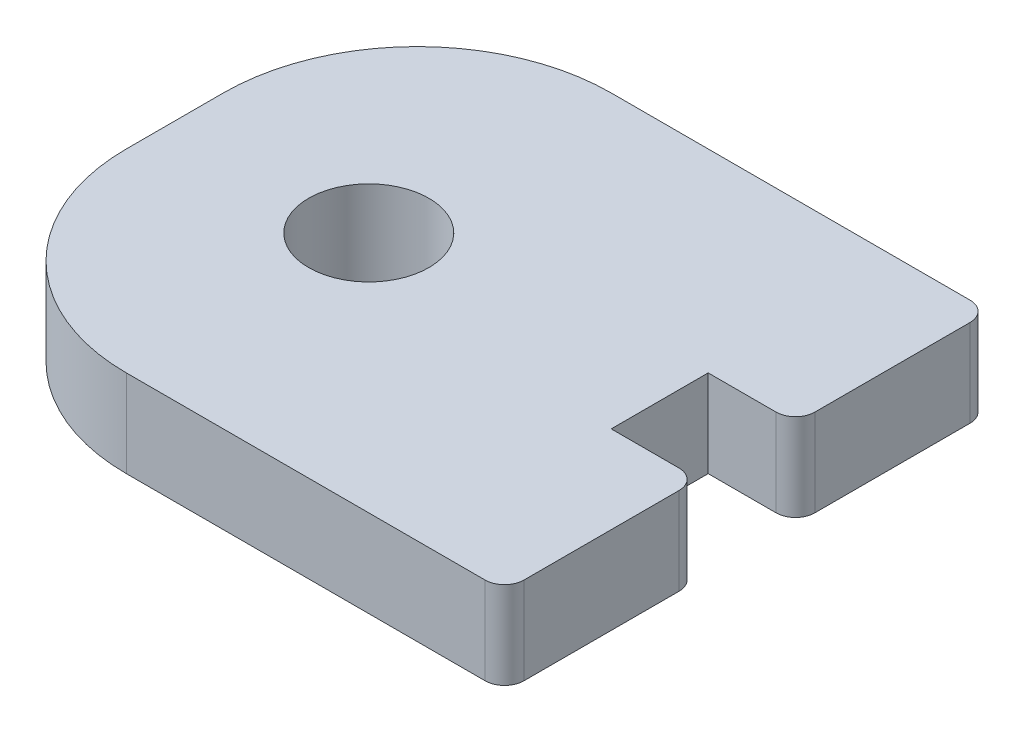
SolidWorks part; units mm, degrees
ref_plane "Front Plane" through (0, 0, 0) normal (0, 0, 1) x (1, 0, 0)
ref_plane "Top Plane" through (0, 0, 0) normal (0, 1, 0) x (1, 0, 0)
ref_plane "Right Plane" through (0, 0, 0) normal (1, 0, 0) x (0, 0, -1)
sketch "Sketch1" plane through (0, 0, 0) normal (0, 1, 0) x (1, 0, 0)
  line L0 (10, 25) -> (10, 0) construction
  line L1 (10, 0) -> (25, 0)
  line L2 (0, 10) -> (0, 15)
  line L3 (10, 25) -> (25, 25)
  line L4 (25, 10) -> (25, 15)
  line L6 (25, 25) -> (28.5, 25)
  line L8 (25, 15) -> (28.5, 15)
  line L9 (29.5, 24) -> (29.5, 16)
  line L10 (25, 0) -> (28.5, 0)
  line L12 (25, 10) -> (28.5, 10)
  line L13 (29.5, 1) -> (29.5, 9)
  circle A0 centre (10, 12.5) radius 3.1
  arc A1 (10, 0) -> (0, 10) centre (10, 10) cw
  arc A2 (0, 15) -> (10, 25) centre (10, 15) cw
  arc A3 (28.5, 0) -> (29.5, 1) centre (28.5, 1) ccw
  arc A4 (28.5, 10) -> (29.5, 9) centre (28.5, 9) cw
  arc A5 (28.5, 15) -> (29.5, 16) centre (28.5, 16) ccw
  arc A6 (28.5, 25) -> (29.5, 24) centre (28.5, 24) cw
  point P11 (0, 0)
  point P14 (0, 25)
  point P23 (29.5, 0)
  point P26 (29.5, 10)
  point P29 (29.5, 15)
  point P32 (29.5, 25)
  dimension "D4" = 10
  dimension "D9" = 1
  dimension "D1" = 25
  dimension "D2" = 25
  dimension "D3" = 10
  dimension "D5" = 4.5
  dimension "D6" = 4.5
  dimension "D7" = 10
  dimension "D8" = 10
extrude "Boss-Extrude1" add sketch "Sketch1" along normal blind 4.5
